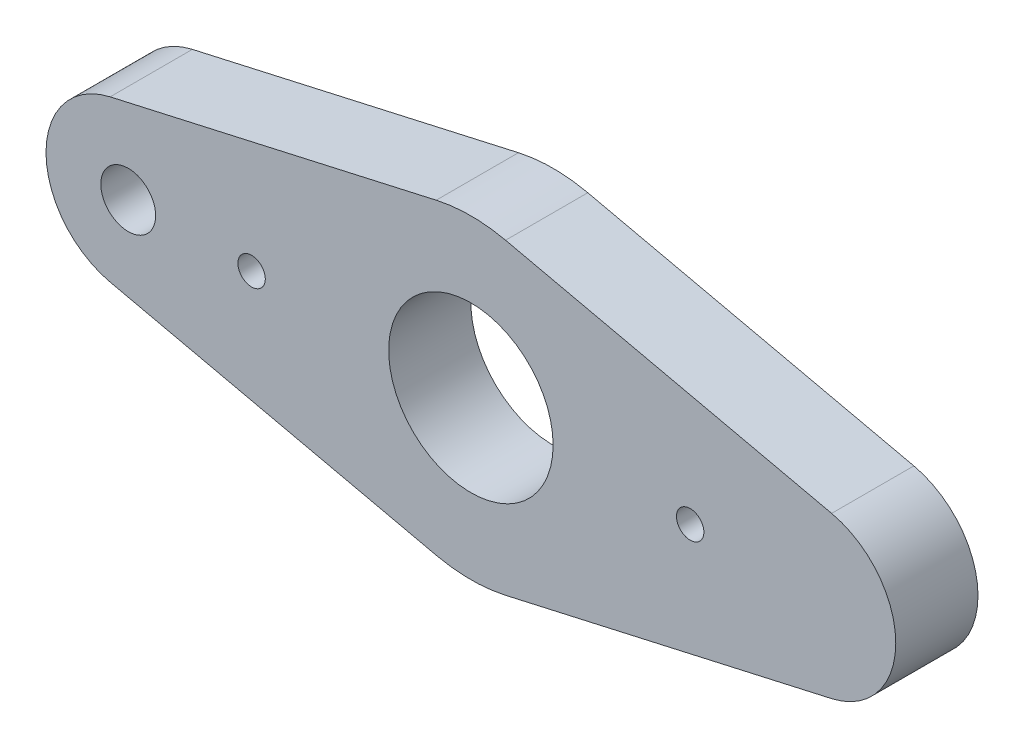
SolidWorks part; units mm, degrees
ref_plane "Alzado" through (0, 0, 0) normal (0, 0, 1) x (1, 0, 0)
ref_plane "Planta" through (0, 0, 0) normal (0, 1, 0) x (1, 0, 0)
ref_plane "Vista lateral" through (0, 0, 0) normal (1, 0, 0) x (0, 0, -1)
sketch "Croquis1" plane through (0, 0, 0) normal (0, 0, 1) x (1, 0, 0)
  line L0 (0, 0) -> (0, 59.5369) construction
  line L1 (0, 0) -> (-19, 0) construction
  line L2 (-26.32, 5.853) -> (-2.53, 11.2182)
  line L3 (-26.32, -5.853) -> (-2.53, -11.2182)
  line L4 (26.32, 5.853) -> (2.53, 11.2182)
  line L5 (26.32, -5.853) -> (2.53, -11.2182)
  line L6 (0, 0) -> (-14.251, 0) construction
  line L7 (0, 0) -> (0, 8.0532) construction
  arc A0 (-2.53, 11.2182) -> (2.53, 11.2182) centre (0, 0) cw
  arc A1 (-26.32, 5.853) -> (-26.32, -5.853) centre (-25, 0) ccw
  circle A2 centre (-25, 0) radius 2
  circle A3 centre (0, 0) radius 6
  arc A4 (-2.53, -11.2182) -> (2.53, -11.2182) centre (0, 0) ccw
  circle A5 centre (-16, 0) radius 1
  arc A6 (26.32, 5.853) -> (26.32, -5.853) centre (25, 0) cw
  circle A7 centre (16, 0) radius 1
  point P15 (0, 11.5)
  point P23 (-31, 0)
  dimension "D1" = 11.5
  dimension "D2" = 25
  dimension "D3" = 4
  dimension "D4" = 12
  dimension "D5" = 6
  dimension "D6" = 16
  dimension "D7" = 2
extrude "Saliente-Extruir1" add sketch "Croquis1" along normal blind 6
